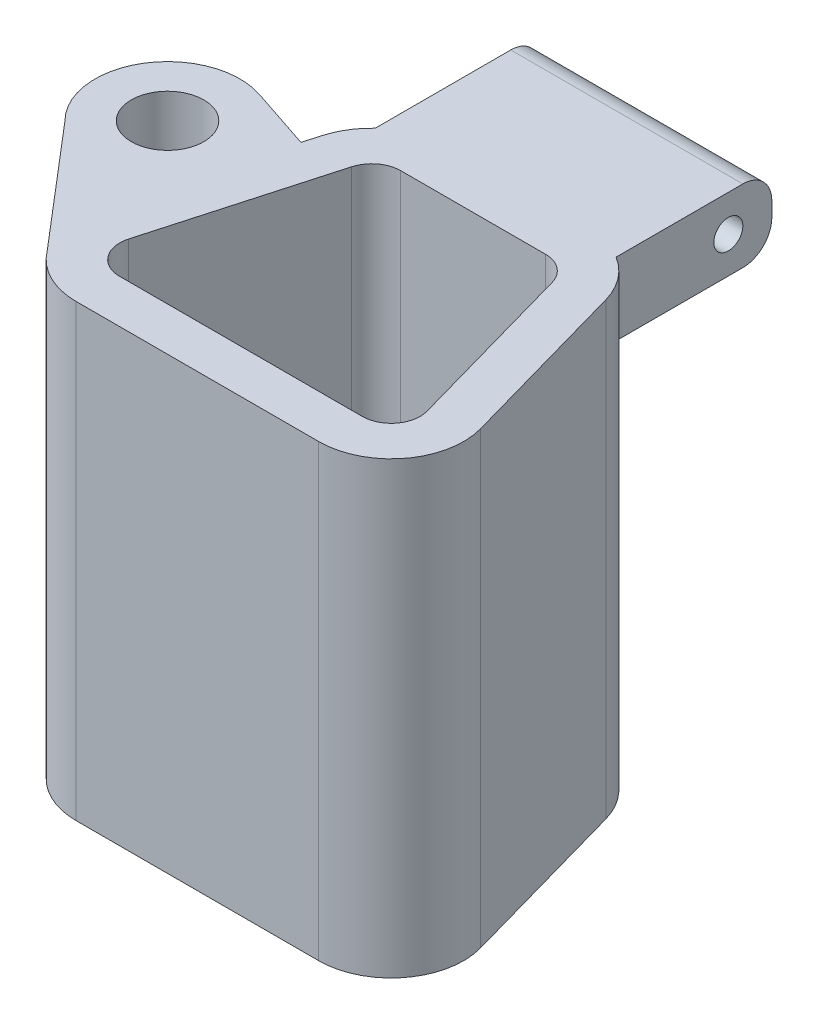
SolidWorks part; units mm, degrees
ref_plane "Front Plane" through (0, 0, 0) normal (0, 0, 1) x (1, 0, 0)
ref_plane "Top Plane" through (0, 0, 0) normal (0, 1, 0) x (1, 0, 0)
ref_plane "Right Plane" through (0, 0, 0) normal (1, 0, 0) x (0, 0, -1)
sketch "Sketch1" plane through (0, 0, 0) normal (0, 1, 0) x (1, 0, 0)
  line L0 (-8.3599, -8) -> (8.3599, -8)
  line L2 (-4.9849, 8) -> (4.9849, 8)
  line L3 (-6.9102, 6.5415) -> (-10.2852, -5.4585)
  line L4 (6.9102, 6.5415) -> (10.2852, -5.4585)
  line L8 (-8.3599, -11) -> (8.3599, -11)
  line L9 (9.7982, 7.3537) -> (13.1732, -4.6463)
  line L10 (-4.9849, 11) -> (4.9849, 11)
  line L11 (-9.7982, 7.3537) -> (-13.1732, -4.6463)
  arc A0 (8.3599, -8) -> (10.2852, -5.4585) centre (8.3599, -6) ccw
  arc A1 (-8.3599, -8) -> (-10.2852, -5.4585) centre (-8.3599, -6) cw
  arc A2 (-4.9849, 8) -> (-6.9102, 6.5415) centre (-4.9849, 6) ccw
  arc A3 (4.9849, 8) -> (6.9102, 6.5415) centre (4.9849, 6) cw
  arc A8 (8.3599, -11) -> (13.1732, -4.6463) centre (8.3599, -6) ccw
  arc A9 (4.9849, 11) -> (9.7982, 7.3537) centre (4.9849, 6) cw
  arc A10 (-4.9849, 11) -> (-9.7982, 7.3537) centre (-4.9849, 6) ccw
  arc A11 (-8.3599, -11) -> (-13.1732, -4.6463) centre (-8.3599, -6) cw
  point P11 (11, -8)
  point P14 (-11, -8)
  point P17 (-6.5, 8)
  point P20 (6.5, 8)
  dimension "D4" = 2
  dimension "D1" = 22
  dimension "D2" = 3
  dimension "D3" = 13
extrude "Boss-Extrude1" add sketch "Sketch1" along normal blind 31
sketch "Sketch2" plane through (0, 0, -11) normal (0, 0, -1) x (-1, 0, 0)
  line L0 (9.7982, 31) -> (4.9849, 31) construction
  line L1 (-7.6014, 26) -> (8.3986, 26)
  line L2 (-7.6014, 26) -> (-7.6014, 31)
  line L3 (-7.6014, 31) -> (8.3986, 31)
  line L4 (8.3986, 26) -> (8.3986, 31)
  line L5 (-7.6014, 26) -> (8.3986, 31) construction
  line L6 (-7.6014, 31) -> (8.3986, 26) construction
  point P0 (0.3986, 28.5)
  dimension "D1" = 16
  dimension "D2" = 5
  dimension "D3" = 2.5
extrude "Boss-Extrude2" add sketch "Sketch2" along normal blind 10 and the other way up to surface other way up to face at (0, 15.5, -8)
sketch "Sketch3" plane through (-8.3986, 0, 0) normal (-1, 0, 0) x (0, 0, 1)
  line L0 (-9.6533, 31) -> (-21, 31) construction
  line L1 (-21, 26) -> (-21, 31) construction
  circle A0 centre (-18, 28.5) radius 1
  dimension "D1" = 2
  dimension "D2" = 2.5
  dimension "D3" = 3
extrude "Cut-Extrude1" cut sketch "Sketch3" against normal through all
fillet "Fillet1" radius 2 2 edges at (-0.3986, 26, -21) (-0.3986, 31, -21)
sketch "Sketch4" plane through (0, 31, 0) normal (0, 1, 0) x (1, 0, 0)
  line L0 (-19.5355, -0.5966) -> (-12.3454, -9.0192)
  line L1 (-14.4209, 7.683) -> (-10.1092, 6.2478)
  line L2 (-9.7982, 7.3537) -> (-13.1732, -4.6463) construction
  line L3 (-12.3454, -9.0192) -> (-10.1092, 6.2478)
  arc A0 (-14.4209, 7.683) -> (-19.5355, -0.5966) centre (-16, 2.9389) ccw
  circle A1 centre (-16, 2.9389) radius 2.5
  arc A2 (-13.1732, -4.6463) -> (-8.3599, -11) centre (-8.3599, -6) ccw construction
  dimension "D1" = 10
  dimension "D2" = 5
  dimension "D3" = 16
extrude "Boss-Extrude3" add sketch "Sketch4" against normal through all
sketch "Sketch6" plane through (0.8639, 0, -2.5953) normal (0.3158, 0, -0.9488) x (-0.9488, 0, -0.3158)
  line L0 (21.1093, 0) -> (21.1093, 31) construction
  line L1 (30.5938, 6.75) -> (11.6247, 6.75)
  line L2 (30.5938, 6.75) -> (30.5938, 24.25)
  line L3 (30.5938, 24.25) -> (11.6247, 24.25)
  line L4 (11.6247, 6.75) -> (11.6247, 24.25)
  line L5 (30.5938, 6.75) -> (11.6247, 24.25) construction
  line L6 (30.5938, 24.25) -> (11.6247, 6.75) construction
  line L7 (11.6247, 0) -> (11.6247, 31) construction
  point P0 (21.1093, 15.5)
  dimension "D1" = 17.5
extrude "Cut-Extrude2" cut sketch "Sketch6" against normal through all
